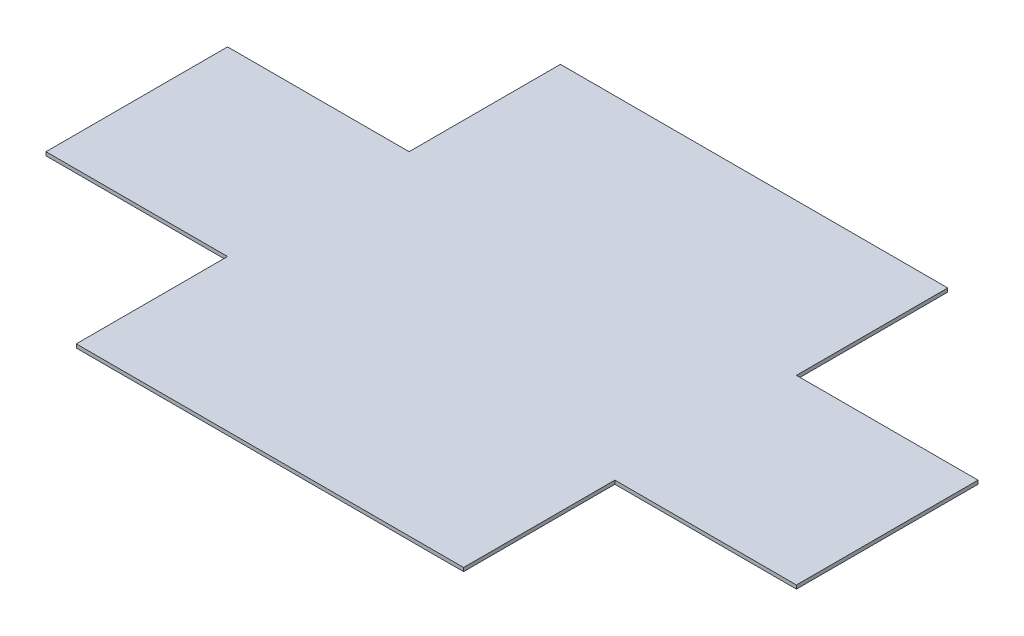
SolidWorks part; units mm, degrees
ref_plane "前视基准面" through (0, 0, 0) normal (0, 0, 1) x (1, 0, 0)
ref_plane "上视基准面" through (0, 0, 0) normal (0, 1, 0) x (1, 0, 0)
ref_plane "右视基准面" through (0, 0, 0) normal (1, 0, 0) x (0, 0, -1)
sketch "草图1" plane through (0, 0, 0) normal (0, 1, 0) x (1, 0, 0)
  line L0 (0, 0) -> (160, -38.7097) construction
  line L1 (-260, 200) -> (260, 200) construction
  line L2 (-260, 200) -> (-260, -200) construction
  line L3 (-260, -200) -> (260, -200) construction
  line L4 (260, 200) -> (260, -200) construction
  line L5 (-260, 200) -> (-160, 123.0769) construction
  line L6 (-260, -200) -> (-160, -123.0769) construction
  line L7 (-310, -75) -> (-160, -75)
  line L8 (-310, -75) -> (-310, 75)
  line L9 (-310, 75) -> (-160, 75)
  line L10 (310, -75) -> (310, 75)
  line L11 (-310, -75) -> (160, 38.7097) construction
  line L12 (-310, 75) -> (-160, 38.7097) construction
  line L13 (-160, -200) -> (160, -200)
  line L14 (-160, -200) -> (-160, -75)
  line L15 (-160, 200) -> (160, 200)
  line L16 (160, -200) -> (160, -75)
  line L17 (-60, -75) -> (0, 0) construction
  line L18 (0, 0) -> (60, -75) construction
  line L19 (-160, 75) -> (-160, 200)
  line L22 (160, 75) -> (310, 75)
  line L24 (97.5, 75) -> (260, 200) construction
  line L25 (160, 75) -> (160, 200)
  line L26 (260, 62.9032) -> (310, 75) construction
  line L27 (260, -62.9032) -> (310, -75) construction
  line L28 (160, -75) -> (310, -75)
  line L29 (160, -123.0769) -> (260, -200) construction
  point P0 (0, 0)
  point P6 (0, 0)
  point P11 (0, 0)
  dimension "D1" = 520
  dimension "D2" = 400
  dimension "D3" = 50
  dimension "D4" = 125
  dimension "D5" = 100
extrude "凸台-拉伸1" add sketch "草图1" along normal blind 3
